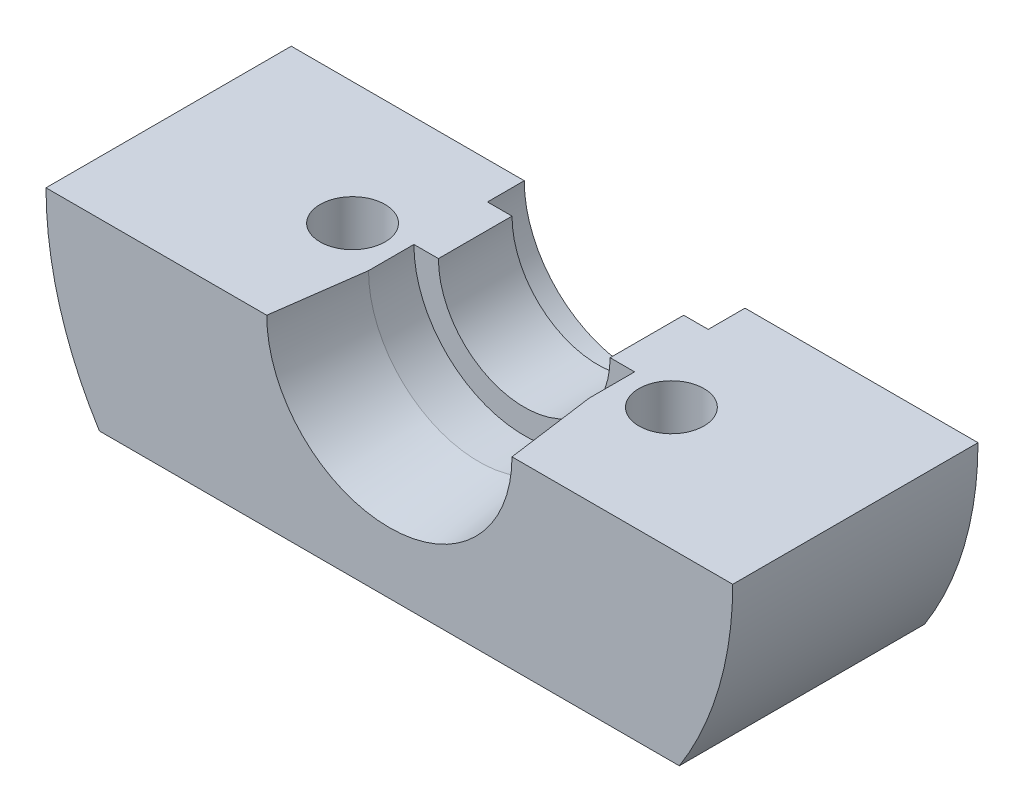
SolidWorks part; units mm, degrees
ref_plane "Plan de face" through (0, 0, 0) normal (0, 0, 1) x (1, 0, 0)
ref_plane "Plan de dessus" through (0, 0, 0) normal (0, 1, 0) x (1, 0, 0)
ref_plane "Plan de droite" through (0, 0, 0) normal (1, 0, 0) x (0, 0, -1)
sketch "Esquisse1" plane through (0, 0, 0) normal (0, 0, 1) x (1, 0, 0)
  line L0 (-10, 0) -> (-30.75, 0) construction
  line L1 (30.75, 0) -> (10, 0) construction
  line L2 (-28, 0) -> (28, 0)
  arc A0 (-28, 0) -> (28, 0) centre (0, 0) ccw
  dimension "D1" = 28
extrude "Boss.-Extru.1" add sketch "Esquisse1" against normal blind 20
sketch "Esquisse2" plane through (0, 0, 0) normal (0, 1, 0) x (1, 0, 0)
  line L0 (0, 0) -> (0, 20) construction
  line L1 (28, 20) -> (-28, 20) construction
  line L19 (12.15, 24) -> (12.15, 25)
  line L20 (12.15, 25) -> (0, 25)
  line L21 (0, 25) -> (0, 0)
  line L22 (0, 0) -> (10, 0)
  line L23 (10, 0) -> (9, 7.3)
  line L24 (9, 7.3) -> (9, 11)
  line L25 (9, 11) -> (7, 11)
  line L26 (7, 11) -> (7, 17)
  line L27 (7, 17) -> (9, 17)
  line L28 (9, 17) -> (9, 20)
  line L29 (9, 20) -> (7.25, 20)
  line L30 (7.25, 20) -> (7.25, 21.5)
  line L31 (7.25, 21.5) -> (9, 21.5)
  line L32 (9, 21.5) -> (9, 22.5)
  line L33 (9, 22.5) -> (7.25, 22.5)
  line L34 (7.25, 22.5) -> (7.25, 24)
  line L35 (7.25, 24) -> (12.15, 24)
  line L36 (12.15, 24) -> (12.15, 25)
  line L37 (12.15, 25) -> (0, 25)
  line L38 (0, 25) -> (0, 0)
  line L39 (0, 0) -> (10, 0)
  line L40 (10, 0) -> (9, 7.3)
  line L41 (9, 7.3) -> (9, 11)
  line L42 (9, 11) -> (7, 11)
  line L43 (7, 11) -> (7, 17)
  line L44 (7, 17) -> (9, 17)
  line L45 (9, 17) -> (9, 20)
  line L46 (9, 20) -> (7.25, 20)
  line L47 (7.25, 20) -> (7.25, 21.5)
  line L48 (7.25, 21.5) -> (9, 21.5)
  line L49 (9, 21.5) -> (9, 22.5)
  line L50 (9, 22.5) -> (7.25, 22.5)
  line L51 (7.25, 22.5) -> (7.25, 24)
  line L52 (7.25, 24) -> (12.15, 24)
  dimension "D1" = 0
revolve "Enlèvement de matière-Révolution1" cut sketch "Esquisse2" angle 360 about L0
hole_wizard "Dégagement M51" positions "Esquisse3" profile "Esquisse4" hole size "M5" standard "Ansi Metric"
sketch "Esquisse3" plane through (0, 0, 0) normal (0, 1, 0) x (1, 0, 0)
  line L7 (-28, 20) -> (-28, 0) construction
  line L8 (28, 20) -> (28, 0) construction
  line L9 (28, 0) -> (10, 0) construction
  point P0 (-13, 10)
  point P2 (13, 10)
  dimension "D1" = 15
  dimension "D2" = 15
  dimension "D3" = 10
sketch "Esquisse4" plane through (-13, 0, -10) normal (1, 0, 0) x (0, 0, 1)
  line L0 (0, 0) -> (0, 46.5923)
  line L1 (0, 46.5923) -> (2.65, 45)
  line L2 (2.65, 45) -> (2.65, 0)
  line L5 (2.65, 0) -> (0, 0)
  line L10 (0, 46.5923) -> (-2.65, 45) construction
  line L11 (0, -6.35) -> (0, 107.95) construction
  dimension "Diamètre du perçage" = 5.3
  dimension "Profondeur du perçage" = 45
  dimension "Angle de pointe" = 118
ref_plane "Plan1" through (0, -28, 0) normal (0, -1, 0) x (0, 0, 1)
sketch "Esquisse5" plane through (0, -28, 0) normal (0, -1, 0) x (0, 0, 1)
  circle A0 centre (-10, 13) radius 4.5
  circle A1 centre (-10, -13) radius 4.5
  dimension "D1" = 9
  dimension "D2" = 9
extrude "Enlèv. mat.-Extru.1" cut sketch "Esquisse5" against normal blind 20
sketch "Esquisse6" plane through (0, 0, 0) normal (0, 0, 1) x (1, 0, 0)
  line L0 (-23.6432, -15) -> (23.6432, -15)
  line L1 (-10, 0) -> (-28, 0) construction
  arc A0 (-28, 0) -> (28, 0) centre (0, 0) ccw construction
  arc A1 (-23.6432, -15) -> (23.6432, -15) centre (0, 0) ccw
  dimension "D1" = 15
extrude "Enlèv. mat.-Extru.2" cut sketch "Esquisse6" against normal blind 20
